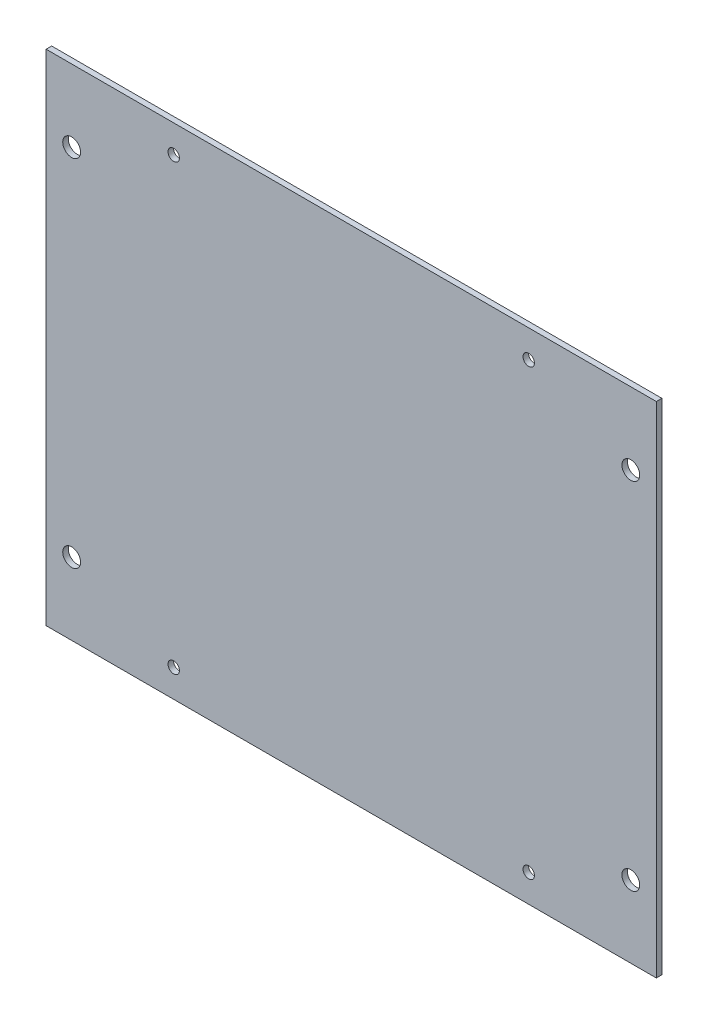
SolidWorks part; units mm, degrees
material "Perspex (TM) GS Acrylic Cast Sheet"
ref_plane "Front Plane" through (0, 0, 0) normal (0, 0, 1) x (1, 0, 0)
ref_plane "Top Plane" through (0, 0, 0) normal (0, 1, 0) x (1, 0, 0)
ref_plane "Right Plane" through (0, 0, 0) normal (1, 0, 0) x (0, 0, -1)
sketch "Sketch1" plane through (0, 0, 0) normal (0, 0, 1) x (1, 0, 0)
  line L1 (-457.2, -304.8) -> (457.2, -304.8)
  line L2 (-457.2, -304.8) -> (-457.2, 304.8)
  line L3 (-457.2, 304.8) -> (457.2, 304.8)
  line L4 (457.2, -304.8) -> (457.2, 304.8)
  line L5 (0, 304.8) -> (0, -304.8) construction
  line L6 (-457.2, 0) -> (457.2, 0) construction
  point P0 (0, 0)
  point P4 (-320.04, 0)
  point P5 (320.04, 0)
  point P6 (0, 213.36)
  point P7 (0, -213.36)
  dimension "Length" = 914.4
  dimension "Width" = 609.6
  dimension "Break" = 137.16
  dimension "D2" = 137.16
  dimension "D1" = 91.44
  dimension "D3" = 91.44
sketch "Sketch2" plane through (0, 0, 0) normal (1, 0, 0) x (0, 0, -1)
  line L0 (-0.7938, -304.8) -> (0.7938, -304.8)
  dimension "Thickness" = 1.5875
sketch "Sketch3" plane through (0, 0, 0) normal (0, 0, 1) x (1, 0, 0)
  line L0 (-457.2, -304.8) -> (-457.2, 304.8) construction
  line L1 (-457.2, -304.8) -> (457.2, -304.8) construction
  line L2 (457.2, -304.8) -> (457.2, 304.8) construction
  line L3 (-457.2, 304.8) -> (457.2, 304.8) construction
  line L4 (-457.2, -304.8) -> (-457.2, 304.8)
  line L5 (-457.2, -304.8) -> (457.2, -304.8)
  line L6 (457.2, -304.8) -> (457.2, 304.8)
  line L7 (-457.2, 304.8) -> (457.2, 304.8)
extrude "Boss-Extrude1" add sketch "Sketch3" along normal mid plane 1.5875
sketch "Sketch4" plane through (0, 0, -0.7937) normal (0, 0, -1) x (-1, 0, 0)
  line L0 (387.3498, -19.1072) -> (212.7248, -19.1072)
  line L1 (212.7248, -19.1072) -> (212.7248, 123.7678)
  line L2 (212.7248, 123.7678) -> (387.3498, 123.7678)
  line L3 (387.3498, 123.7678) -> (387.3498, -19.1072)
extrude "Cut-Extrude1" cut sketch "Sketch4" against normal blind 2.54 flip side to cut
hole_wizard "#4 Clearance Hole1" positions "Sketch9" profile "Sketch10" hole size "#4" standard "ANSI Inch" end condition through all
sketch "Sketch9" plane through (0, 0, -0.7937) normal (0, 0, -1) x (-1, 0, 0)
  point P34 (350.8373, 115.8303)
  point P37 (249.2373, 115.8303)
  point P40 (249.2373, -11.1697)
  point P43 (350.8373, -11.1697)
sketch "Sketch10" plane through (-350.8373, 115.8303, -0.7937) normal (1, 0, 0) x (0, 1, 0)
  line L0 (0, 0) -> (0, 1.5875)
  line L1 (0, 1.5875) -> (1.6319, 1.5875)
  line L2 (1.6319, 1.5875) -> (1.6319, 0)
  line L5 (1.6319, 0) -> (0, 0)
  line L11 (0, -6.35) -> (0, 107.95) construction
  dimension "Thru Hole Dia." = 3.2639
  dimension "Thru Hole Depth" = 1.5875
hole_wizard "#10 Clearance Hole1" positions "Sketch11" profile "Sketch12" hole size "#10" standard "ANSI Inch" end condition through all
sketch "Sketch11" plane through (0, 0, -0.7937) normal (0, 0, -1) x (-1, 0, 0)
  point P0 (220.0273, 1.5303)
  point P3 (220.0273, 103.13)
  point P6 (380.0473, 103.1303)
  point P9 (380.0473, 1.5306)
sketch "Sketch12" plane through (-220.0273, 1.5303, -0.7937) normal (1, 0, 0) x (0, 1, 0)
  line L0 (0, 0) -> (0, 1.5875)
  line L1 (0, 1.5875) -> (2.5527, 1.5875)
  line L2 (2.5527, 1.5875) -> (2.5527, 0)
  line L5 (2.5527, 0) -> (0, 0)
  line L11 (0, -6.35) -> (0, 107.95) construction
  dimension "Thru Hole Dia." = 5.1054
  dimension "Thru Hole Depth" = 1.5875
equation "\"D1@Boss-Extrude1\"=\"thickness@sketch2\""
equation "\"Break@Sketch1\" = \"Length@Sketch1\" * 0.15"
equation "\"D2@Sketch1\" = \"Break@Sketch1\""
equation "\"D1@Sketch1\"=\"Width@Sketch1\"*0.15"
equation "\"D3@Sketch1\"=\"D1@Sketch1\""
